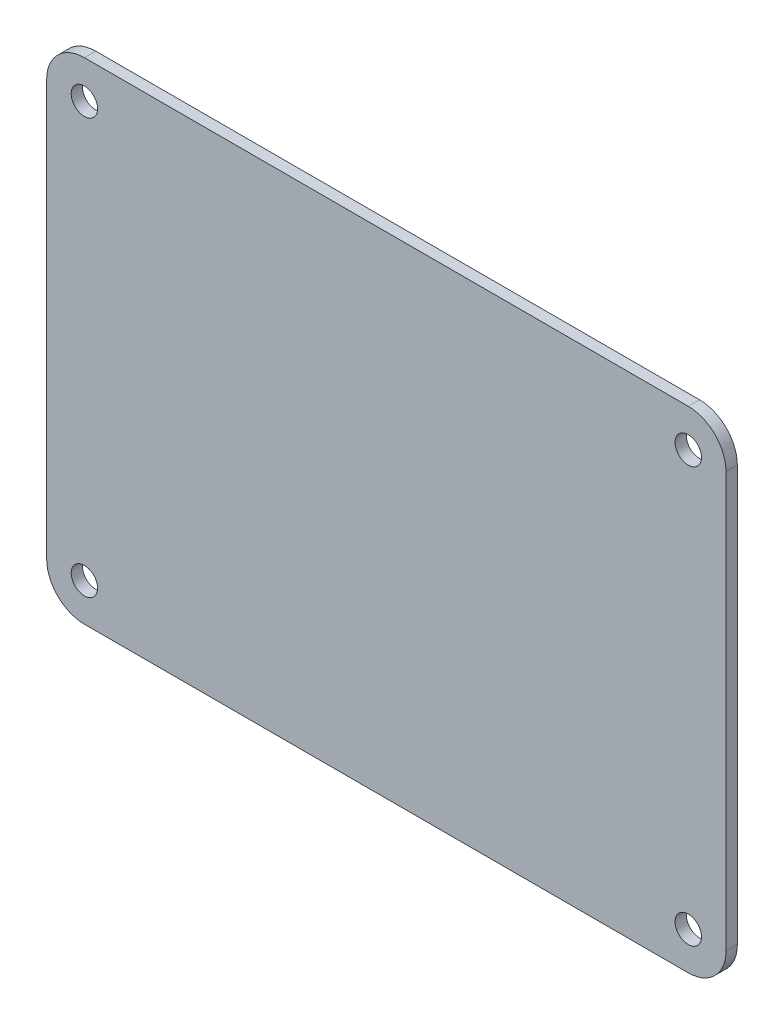
SolidWorks part; units mm, degrees
ref_plane "前视基准面" through (0, 0, 0) normal (0, 0, 1) x (1, 0, 0)
ref_plane "上视基准面" through (0, 0, 0) normal (0, 1, 0) x (1, 0, 0)
ref_plane "右视基准面" through (0, 0, 0) normal (1, 0, 0) x (0, 0, -1)
sketch "草图1" plane through (0, 0, 0) normal (0, 0, 1) x (1, 0, 0)
  line L1 (-90, 65) -> (90, 65)
  line L2 (-90, 65) -> (-90, -65)
  line L3 (-90, -65) -> (90, -65)
  line L4 (90, 65) -> (90, -65)
  line L5 (-90, 65) -> (90, -65) construction
  line L6 (-90, -65) -> (90, 65) construction
  point P0 (0, 0)
  dimension "D1" = 180
  dimension "D2" = 130
extrude "凸台-拉伸1" add sketch "草图1" along normal blind 3
fillet "圆角1" radius 10 4 edges at (-90, 65, 1.5) (90, 65, 1.5) (90, -65, 1.5) (-90, -65, 1.5)
sketch "草图2" plane through (0, 0, 3) normal (0, 0, 1) x (1, 0, 0)
  line L0 (-90, 55) -> (-90, -55) construction
  line L1 (80, 65) -> (-80, 65) construction
  line L2 (90, -55) -> (90, 55) construction
  line L3 (-80, -65) -> (80, -65) construction
  circle A0 centre (-80, 55) radius 3.5
  circle A1 centre (-80, -55) radius 3.5
  circle A2 centre (80, 55) radius 3.5
  circle A3 centre (80, -55) radius 3.5
  dimension "D1" = 7
  dimension "D2" = 10
  dimension "D3" = 10
  dimension "D4" = 10
  dimension "D5" = 10
  dimension "D6" = 10
  dimension "D7" = 10
  dimension "D8" = 10
  dimension "D9" = 10
extrude "切除-拉伸1" cut sketch "草图2" against normal through all
